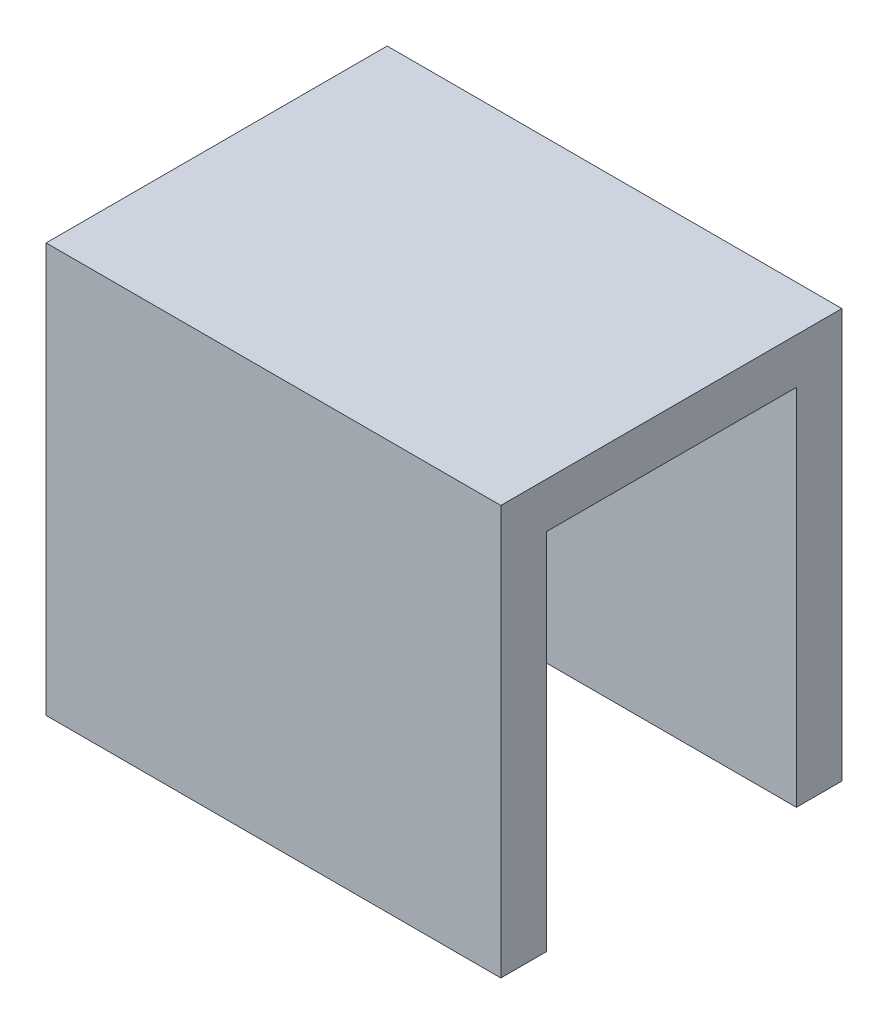
SolidWorks part; units mm, degrees
ref_plane "Front Plane" through (0, 0, 0) normal (0, 0, 1) x (1, 0, 0)
ref_plane "Top Plane" through (0, 0, 0) normal (0, 1, 0) x (1, 0, 0)
ref_plane "Right Plane" through (0, 0, 0) normal (1, 0, 0) x (0, 0, -1)
sketch "Sketch1" plane through (0, 0, 0) normal (1, 0, 0) x (0, 0, -1)
  line L0 (-6.7119, 0) -> (-6.7119, 18)
  line L1 (-6.7119, 18) -> (8.2881, 18)
  line L2 (8.2881, 18) -> (8.2881, 0)
  line L3 (8.2881, 0) -> (6.2881, 0)
  line L4 (6.2881, 0) -> (6.2881, 16)
  line L5 (6.2881, 16) -> (-4.7119, 16)
  line L6 (-4.7119, 16) -> (-4.7119, 0)
  line L7 (-4.7119, 0) -> (-6.7119, 0)
  dimension "D1" = 15
  dimension "D2" = 2
  dimension "D3" = 2
  dimension "D4" = 18
extrude "Boss-Extrude1" add sketch "Sketch1" along normal blind 20
